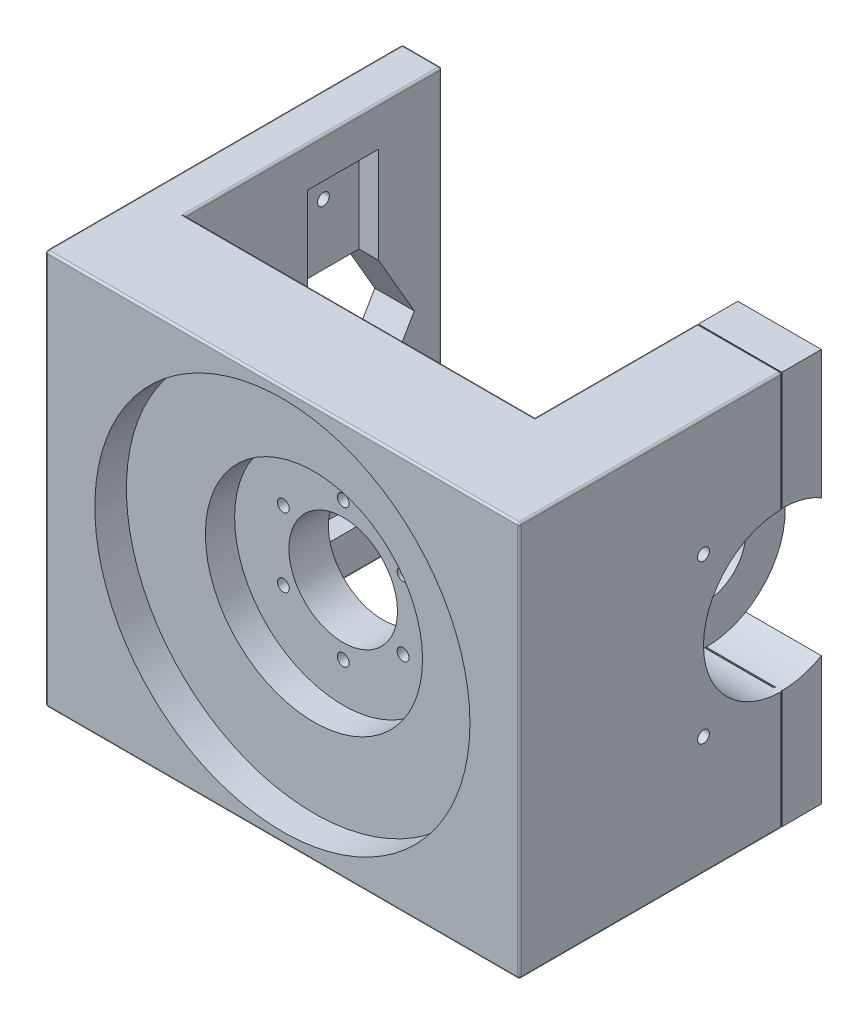
SolidWorks part; units mm, degrees
ref_plane "前视基准面" through (0, 0, 0) normal (0, 0, 1) x (1, 0, 0)
ref_plane "上视基准面" through (0, 0, 0) normal (0, 1, 0) x (1, 0, 0)
ref_plane "右视基准面" through (0, 0, 0) normal (1, 0, 0) x (0, 0, -1)
sketch "草图1" plane through (0, 0, 0) normal (0, 0, 1) x (1, 0, 0)
  circle A0 centre (0, 0) radius 100
  circle A1 centre (0, 0) radius 95
extrude "凸台-拉伸1" add sketch "草图1" along normal blind 50.8
sketch "草图2" plane through (0, 0, 0) normal (0, 0, 1) x (1, 0, 0)
  circle A0 centre (0, 0) radius 95
  circle A1 centre (0, 0) radius 55
extrude "凸台-拉伸2" add sketch "草图2" along normal blind 34.8
sketch "草图4" plane through (0, 0, 0) normal (0, 0, 1) x (1, 0, 0)
  circle A0 centre (0, 0) radius 55
  circle A1 centre (0, 0) radius 27.5
  circle A2 centre (0, 0) radius 35
  circle A3 centre (0, -35) radius 3
extrude "凸台-拉伸3" add sketch "草图4" along normal blind 20 contours A0 A3 A2 | A3 A2 A1
sketch "草图5" plane through (0, 0, 0) normal (0, 0, -1) x (-1, 0, 0)
  circle A0 centre (0, -35) radius 3
  circle A1 centre (0, 35) radius 3
  dimension "D1" = 70
extrude "切除-拉伸2" cut sketch "草图5" against normal blind 20 contours A1
pattern_circular "阵列(圆周)3" count 6 over 360 about axis through (0, 0, 0) along (0, 0, 1) of "切除-拉伸2"
sketch "草图6" plane through (0, 0, 0) normal (0, 0, -1) x (-1, 0, 0)
  line L1 (-200, -100) -> (200, -100)
  line L2 (-200, -100) -> (-200, 100)
  line L3 (-200, 100) -> (200, 100)
  line L4 (200, -100) -> (200, 100)
  line L5 (-200, -100) -> (200, 100) construction
  line L6 (-200, 100) -> (200, -100) construction
  circle A0 centre (0, 0) radius 100
  point P0 (0, 0)
  circle M10 centre (0, 0) radius 100
  dimension "D1" = 200
  dimension "D2" = 400
extrude "凸台-拉伸4" add sketch "草图6" against normal blind 50.8 contours L1 L4 L3 M10 | L3 L2 L1 M10
sketch "草图7" plane through (0, 0, 0) normal (0, 0, -1) x (-1, 0, 0)
  line L1 (40, 100) -> (120, 100)
  line L2 (40, 100) -> (40, -100)
  line L3 (40, -100) -> (120, -100)
  line L4 (120, 100) -> (120, -100)
  line L5 (40, 100) -> (120, -100) construction
  line L6 (40, -100) -> (120, 100) construction
  point P0 (80, 0)
  dimension "D1" = 200
  dimension "D2" = 80
  dimension "D3" = 80
extrude "凸台-拉伸5" add sketch "草图7" along normal blind 100
sketch "草图8" plane through (0, 0, 0) normal (0, 0, -1) x (-1, 0, 0)
  line L1 (120, 100) -> (200, 100)
  line L2 (120, 100) -> (120, -100)
  line L3 (120, -100) -> (200, -100)
  line L4 (200, 100) -> (200, -100)
  line L5 (120, 100) -> (200, -100) construction
  line L6 (120, -100) -> (200, 100) construction
  point P0 (160, 0)
  dimension "D1" = 80
extrude "切除-拉伸3" cut sketch "草图8" against normal blind 100
mirror "镜向2" about plane through (0, 0, 0) normal (1, 0, 0) of "切除-拉伸3"
sketch "草图11" plane through (0, 0, -100) normal (0, 0, -1) x (-1, 0, 0)
  line L0 (100, 100) -> (100, -100)
  line L1 (120, 100) -> (40, 100) construction
  line L2 (40, -100) -> (120, -100) construction
  line M3 (120, 100) -> (40, 100)
  line M4 (40, 100) -> (40, -100)
  line M5 (40, -100) -> (120, -100)
  dimension "D1" = 20
extrude "切除-拉伸5" cut sketch "草图11" against normal blind 100 and the other way through all contours L0 M3 M4 M5
sketch "草图15" plane through (0, 0, -100) normal (0, 0, -1) x (-1, 0, 0)
  line L1 (100, -100) -> (120, -100)
  line L2 (100, -100) -> (100, 100)
  line L3 (100, 100) -> (120, 100)
  line L4 (120, -100) -> (120, 100)
  line L5 (100, -100) -> (120, 100) construction
  line L6 (100, 100) -> (120, -100) construction
  point P0 (110, 0)
extrude "凸台-拉伸6" add sketch "草图15" along normal blind 30
sketch "草图16" plane through (-100, 0, 0) normal (1, 0, 0) x (0, 0, -1)
  line L0 (30, 100) -> (30, -100)
  line L1 (130, 100) -> (0, 100) construction
  line L2 (130, -100) -> (0, -100) construction
  line L3 (130, 100) -> (130, -100) construction
  line L4 (30, 0) -> (130, 0)
  line L5 (80, 100) -> (80, -100)
  line L7 (116, 0) -> (98, 31.1769)
  line L8 (98, 31.1769) -> (62, 31.1769)
  line L9 (62, 31.1769) -> (44, 0)
  line L10 (44, 0) -> (62, -31.1769)
  line L11 (62, -31.1769) -> (98, -31.1769)
  line L12 (98, -31.1769) -> (116, 0)
  circle A0 centre (80, 0) radius 36 construction
  point P13 (80, 0)
  dimension "D1" = 100
extrude "切除-拉伸13" cut sketch "草图16" against normal blind 20 contours L10 L11 L5 L4 | L8 L9 L4 L5 | L7 L8 L5 L4 | L11 L12 L4 L5
sketch "草图19" plane through (-100, 0, 0) normal (1, 0, 0) x (0, 0, -1)
  line L1 (62, 80) -> (98, 80)
  line L2 (62, 80) -> (62, -80)
  line L3 (62, -80) -> (98, -80)
  line L4 (98, 80) -> (98, -80)
  line L5 (62, 80) -> (98, -80) construction
  line L6 (62, -80) -> (98, 80) construction
  point P0 (80, 0)
  dimension "D1" = 36
  dimension "D2" = 160
extrude "切除-拉伸14" cut sketch "草图19" against normal blind 10
sketch "草图20" plane through (-110, 0, 0) normal (1, 0, 0) x (0, 0, -1)
  line L0 (98, 80) -> (62, 80) construction
  circle A0 centre (80, 62) radius 3
  dimension "D1" = 18
extrude "切除-拉伸15" cut sketch "草图20" against normal blind 10
mirror "镜向6" about plane through (0, 0, 0) normal (0, 1, 0) of "切除-拉伸15"
sketch "草图21" plane through (0, 0, 0) normal (0, 0, -1) x (-1, 0, 0)
  line L0 (-120, 100) -> (-120, -100) construction
  line L1 (-141.45, -100) -> (-98.55, -100)
  line L2 (-141.45, -100) -> (-141.45, 100)
  line L3 (-141.45, 100) -> (-98.55, 100)
  line L4 (-98.55, -100) -> (-98.55, 100)
  line L5 (-141.45, -100) -> (-98.55, 100) construction
  line L6 (-141.45, 100) -> (-98.55, -100) construction
  line L7 (-120, 100) -> (100, 100) construction
  line L8 (-120, 100) -> (-120, -100)
  point P0 (-120, 0)
  line M9 (-120, 100) -> (-120, -100)
  line M10 (-120, -100) -> (100, -100)
  line M12 (100, 100) -> (-120, 100)
  dimension "D1" = 42.9
ref_plane "基准面1" through (98.55, 0, 0) normal (1, 0, 0) x (0, 0, -1)
extrude "凸台-拉伸9" add sketch "草图21" along normal blind 82.5 contours L4 M10 M12 M9
sketch "草图26" plane through (98.55, 0, 0) normal (-1, 0, 0) x (0, 0, 1)
  line L0 (-82.5, -100) -> (-82.5, 100) construction
  circle A0 centre (-82.5, 0) radius 40
extrude "切除-拉伸19" cut sketch "草图26" against normal blind 17.45
sketch "草图27" plane through (116, 0, 0) normal (-1, 0, 0) x (0, 0, 1)
  line L0 (-82.5, -40) -> (-82.5, 40) construction
  circle A0 centre (-82.5, 0) radius 17.5
extrude "切除-拉伸20" cut sketch "草图27" against normal blind 17.45
mirror "镜向8" about plane through (98.55, 0, 0) normal (1, 0, 0) of "凸台-拉伸9", "切除-拉伸19", "切除-拉伸20"
fillet "圆角1" radius 1 25 edges at (120, 100, -15.85) (120, -100, -15.85) (98.55, -100, -82.5) (98.55, 100, -82.5) (120, 58.75, -82.5) (116, -28.75, -82.5) (98.55, 40, -82.5) (98.55, -40, -82.5) (116, 28.75, -82.5) (116, 0, -65) (120, -58.75, -82.5) (120, 0, -65) (118, -17.5, -82.5) (118, 17.5, -82.5) (77.1, 58.75, -82.5) (77.1, -100, -41.25) (77.1, 100, -41.25) (81.1, 28.75, -82.5) (81.1, 0, -42.5) (81.1, -28.75, -82.5) (81.1, 0, -65) (77.1, -58.75, -82.5) (79.1, 17.5, -82.5) (77.1, 0, -65) (79.1, -17.5, -82.5)
fillet "圆角2" radius 1 16 edges at (119.7071, -99.7071, 50.8) (119.7071, 99.7071, 50.8) (-120, 0, 50.8) (-0.5, -100, 50.8) (-0.5, 100, 50.8) (120, 0, 50.8) (-10.95, -100, 0) (-10.95, 100, 0) (-100, -100, -65) (-120, -100, -39.6) (-110, -100, -130) (-100, 100, -65) (-100, 0, -130) (-110, 100, -130) (-120, 0, -130) (-120, 100, -39.6)
sketch "草图31" plane through (0, 0, -82.5) normal (0, 0, -1) x (-1, 0, 0)
  line L0 (-98.55, 99.44) -> (-98.55, -99.44) construction
  line L1 (-119.7071, 99.7071) -> (-77.3929, 99.7071)
  line L2 (-119.7071, 99.7071) -> (-119.7071, -99.7071)
  line L3 (-119.7071, -99.7071) -> (-77.3929, -99.7071)
  line L4 (-77.3929, 99.7071) -> (-77.3929, -99.7071)
  line L5 (-119.7071, 99.7071) -> (-77.3929, -99.7071) construction
  line L6 (-119.7071, -99.7071) -> (-77.3929, 99.7071) construction
  arc A0 (-78.1, -100) -> (-77.1, -99) centre (-78.1, -99) ccw construction
  point P0 (-98.55, 0)
extrude "凸台-拉伸11" add sketch "草图31" along normal blind 20
sketch "草图32" plane through (120, 0, 0) normal (1, 0, 0) x (0, 0, -1)
  line L0 (82.5, 99.7071) -> (82.5, -99.7071) construction
  circle A0 centre (82.5, 0) radius 40
extrude "切除-拉伸23" cut sketch "草图32" against normal blind 50
sketch "草图33" plane through (77.3929, 0, 0) normal (-1, 0, 0) x (0, 0, 1)
  circle A0 centre (-82.5, 0) radius 40
extrude "凸台-拉伸12" add sketch "草图33" against normal blind 4
sketch "草图34" plane through (77.3929, 0, 0) normal (-1, 0, 0) x (0, 0, 1)
  circle A0 centre (-82.5, 0) radius 20
extrude "切除-拉伸24" cut sketch "草图34" against normal blind 4
sketch "草图39" plane through (120, 0, 0) normal (1, 0, 0) x (0, 0, -1)
  line L1 (2.5, 70) -> (82.5, 70)
  line L2 (2.5, 70) -> (2.5, -70)
  line L3 (2.5, -70) -> (82.5, -70)
  line L4 (82.5, 70) -> (82.5, -70)
  line L5 (2.5, 70) -> (82.5, -70) construction
  line L6 (2.5, -70) -> (82.5, 70) construction
  arc A0 (81.5, 39.9875) -> (81.5, -39.9875) centre (82.5, 0) ccw construction
  circle A1 centre (42.5, 40) radius 3
  circle A2 centre (42.5, -40) radius 3
  point P0 (42.5, 0)
  dimension "D3" = 40
  dimension "D1" = 80
  dimension "D2" = 140
  dimension "D4" = 2
extrude "切除-拉伸26" cut sketch "草图39" against normal blind 20 contours A1 | A2
